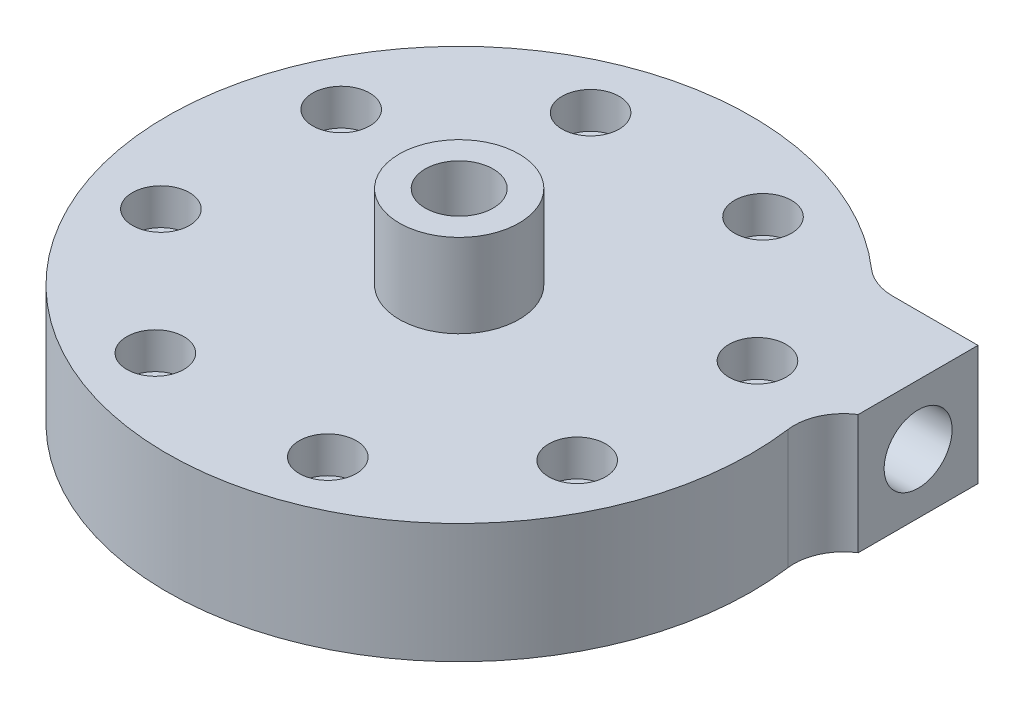
SolidWorks part; units mm, degrees
material "1060 Alloy"
ref_plane "Front" through (0, 0, 0) normal (0, 0, 1) x (1, 0, 0)
ref_plane "Top" through (0, 0, 0) normal (0, 1, 0) x (1, 0, 0)
ref_plane "Right" through (0, 0, 0) normal (1, 0, 0) x (0, 0, -1)
sketch "Sketch1" plane through (0, 0, 0) normal (0, 1, 0) x (1, 0, 0)
  line L0 (0, 0) -> (2.6731, 30.5538) construction
  line L1 (21.117, 30.6705) -> (50.1264, 33.2085) construction
  line L2 (11.6189, 28.3845) -> (50.1264, 28.3845) construction
  line L3 (21.117, 26.0945) -> (50.1264, 23.5565) construction
  line L4 (0, 0) -> (56.1418, -4.9118) construction
  line L5 (21.117, 30.6705) -> (21.117, 28.3845) construction
  line L6 (21.117, 28.3845) -> (21.117, 26.0945) construction
  line L7 (50.1264, 28.3845) -> (50.1264, 33.2085) construction
  line L8 (50.1264, 28.3845) -> (50.1264, 23.5565) construction
  line L9 (60.1264, 28.3845) -> (60.1264, 39.9329)
  line L10 (60.1264, 34.9329) -> (50.1264, 34.9329) construction
  line L11 (60.1264, 34.9329) -> (60.1264, 21.8361) construction
  line L12 (60.1264, 21.8361) -> (50.1264, 21.8361) construction
  line L13 (50.1264, 34.9329) -> (50.1264, 21.8361) construction
  line L14 (60.1264, 39.9329) -> (43.7019, 39.9329)
  line L15 (60.1264, 28.3845) -> (60.1264, 16.8361)
  line L17 (21.117, 30.6705) -> (0, 30.6705) construction
  line L18 (21.117, 26.0945) -> (16.117, 26.0945) construction
  arc A0 (37.1159, 42.408) -> (55.8478, 7.5534) centre (0, 0) ccw
  circle A1 centre (0, 0) radius 30.6705 construction
  arc A2 (55.8478, 7.5534) -> (60.1264, 16.8361) centre (65.2868, 8.8301) cw
  arc A3 (43.7019, 39.9329) -> (37.1159, 42.408) centre (43.7019, 49.9329) cw
  dimension "D1" = 112.7125
  dimension "D2" = 61.341
  dimension "D13" = 9.525
  dimension "D4" = 2.286
  dimension "D3" = 2.29
  dimension "D5" = 5
  dimension "D6" = 5
  dimension "D7" = 5
  dimension "D8" = 9.652
  dimension "D9" = 13.0969
  dimension "D10" = 10
  dimension "D11" = 5
  dimension "D14" = 5
  dimension "D12" = 5
extrude "main body" add sketch "Sketch1" along normal blind 23.0969
ref_plane "body midsection" through (0, 11.5484, 0) normal (0, 1, 0) x (1, 0, 0)
sketch "Sketch7" plane through (0, 23.0969, 0) normal (0, 1, 0) x (1, 0, 0)
  circle A0 centre (0, 0) radius 25.4
  dimension "D1" = 50.8
extrude "inlet boss" add sketch "Sketch7" along normal blind 50.8
sketch "Sketch3" plane through (0, 11.5484, 0) normal (0, 1, 0) x (1, 0, 0)
  line L0 (21.117, 30.6705) -> (0, 30.6705)
  line L1 (0, 30.6705) -> (0, 28.3845)
  line L2 (50.1264, 28.3845) -> (2.4833, 28.3845)
  line L3 (0, 0) -> (2.6731, 30.5538) construction
  line L4 (0, 28.3845) -> (2.4833, 28.3845)
  line L5 (50.1264, 33.2085) -> (50.1264, 34.9329)
  line L6 (50.1264, 34.9329) -> (60.1264, 34.9329)
  line L7 (60.1264, 34.9329) -> (60.1264, 28.3845)
  line L8 (60.1264, 28.3845) -> (50.1264, 28.3845)
  line L9 (21.117, 30.6705) -> (50.1264, 33.2085)
revolve "expansion cone and outlet" cut sketch "Sketch3" angle 360 about L2
sketch "Sketch2" plane through (0, 0, 0) normal (0, 0, 1) x (1, 0, 0)
  line L0 (-56.3562, 11.5484) -> (56.3562, 11.5484) construction
  line L1 (-56.3562, 23.0969) -> (-56.3562, 0) construction
  line L2 (56.3562, 0) -> (56.3562, 23.0969) construction
  line L3 (0, 0) -> (0, 23.0969) construction
  line L4 (25.4, 23.0969) -> (-25.4, 23.0969) construction
  line L5 (0, 18.6817) -> (0, 9.0936)
  line L6 (0, 9.0936) -> (26.67, 9.0936) construction
  line L7 (5.461, 18.6817) -> (5.565, 19.1708) construction
  line L8 (26.67, 14.1736) -> (5.461, 14.1736) construction
  line L9 (26.67, 9.0936) -> (26.67, 14.1736) construction
  line L10 (0, 19.1929) -> (0, 39.1929)
  line L11 (26.67, 14.1736) -> (5.461, 18.6817) construction
  line L12 (5.461, 18.6817) -> (0, 18.6817) construction
  line L13 (5.461, 18.6817) -> (5.461, 9.0936) construction
  line L14 (0, 9.0936) -> (0, 7.0936) construction
  line L15 (0, 7.0936) -> (26.67, 7.0936) construction
  line L16 (26.67, 7.0936) -> (26.67, 9.0936) construction
  line L17 (0, 9.0936) -> (0, 6.5936)
  line L18 (0, 7.0936) -> (0, 6.5936) construction
  line L19 (0, 6.5936) -> (26.67, 6.5936) construction
  line L20 (26.67, 6.5936) -> (26.67, 7.0936) construction
  line L21 (26.67, 6.5936) -> (30.6705, 6.5936) construction
  line L22 (30.6705, 6.5936) -> (30.6705, 13.3233)
  line L23 (26.67, 14.1736) -> (30.6705, 13.3233) construction
  line L24 (5.461, 18.6817) -> (5.461, 19.1929) construction
  line L25 (5.461, 19.1929) -> (0, 19.1929) construction
  line L26 (0, 19.1929) -> (0, 18.6817)
  line L27 (30.6705, 13.3233) -> (30.6705, 13.8344)
  line L28 (30.6705, 13.8344) -> (5.461, 19.1929)
  line L29 (0, 6.5936) -> (0, 0)
  line L30 (0, 0) -> (30.6705, 0)
  line L31 (-56.3562, 0) -> (56.3562, 0) construction
  line L32 (30.6705, 0) -> (30.6705, 6.5936)
  line L33 (30.6705, 13.8344) -> (0, 13.8344) construction
  line L34 (21.117, 13.8344) -> (0, 13.8344) construction
  line L35 (0, 39.1929) -> (6.5484, 39.1929) construction
  line L36 (6.5484, 39.1929) -> (6.5484, 29.1929)
  line L37 (6.5484, 29.1929) -> (5.461, 29.1929)
  line L38 (5.461, 29.1929) -> (5.461, 19.1929)
  line L39 (0, 39.1929) -> (0, 73.8969)
  line L40 (0, 73.8969) -> (25.4, 73.8969)
  line L41 (6.5484, 39.1929) -> (11.5484, 39.1929)
  line L42 (25.4, 73.8969) -> (-25.4, 73.8969) construction
  line L44 (11.5484, 39.1929) -> (11.5484, 23.0969)
  line L46 (25.4, 73.8969) -> (25.4, 23.0969)
  line L47 (25.4, 23.0969) -> (11.5484, 23.0969)
  dimension "D10" = 10
  dimension "D12" = 5
  dimension "D1" = 5.461
  dimension "D2" = 26.67
  dimension "D3" = 9.5881
  dimension "D4" = 5.08
  dimension "D5" = 2
  dimension "D6" = 4.0005
  dimension "D8" = 0.5
  dimension "D9" = 10
  dimension "D11" = 6.5484
revolve "main chamber" cut sketch "Sketch2" angle 360 about L5
sketch "Sketch5" plane through (0, 23.0969, 0) normal (0, 1, 0) x (1, 0, 0)
  line L1 (17.9206, 40.6775) -> (41.4351, 16.0915) construction
  line L3 (11.6189, 28.3845) -> (50.1264, 28.3845) construction
  circle A0 centre (0, 0) radius 44.45 construction
  circle A1 centre (41.4351, 16.0915) radius 2.9766
  circle A2 centre (0, 0) radius 44.45 construction
  circle A3 centre (40.6775, -17.9206) radius 2.9766
  circle A4 centre (0, 0) radius 44.45 construction
  circle A5 centre (16.0915, -41.4351) radius 2.9766
  circle A6 centre (0, 0) radius 44.45 construction
  circle A7 centre (-17.9206, -40.6775) radius 2.9766
  circle A8 centre (0, 0) radius 44.45 construction
  circle A9 centre (-41.4351, -16.0915) radius 2.9766
  circle A10 centre (0, 0) radius 44.45 construction
  circle A11 centre (-40.6775, 17.9206) radius 2.9766
  circle A12 centre (0, 0) radius 44.45 construction
  circle A13 centre (-16.0915, 41.4351) radius 2.9766
  circle A14 centre (0, 0) radius 44.45 construction
  circle A15 centre (17.9206, 40.6775) radius 2.9766
  point P5 (29.6778, 28.3845)
  point P30 (0, 0)
  dimension "D1" = 88.9
  dimension "D2" = 5.9531
  dimension "D4" = 8
sketch "Sketch6" plane through (0, 23.0969, 0) normal (0, 1, 0) x (1, 0, 0)
  circle A0 centre (41.4351, 16.0915) radius 5.5
  circle A1 centre (40.6775, -17.9206) radius 5.5
  circle A2 centre (16.0915, -41.4351) radius 5.5
  circle A3 centre (-17.9206, -40.6775) radius 5.5
  circle A4 centre (-41.4351, -16.0915) radius 5.5
  circle A5 centre (-40.6775, 17.9206) radius 5.5
  circle A6 centre (-16.0915, 41.4351) radius 5.5
  circle A7 centre (17.9206, 40.6775) radius 5.5
  point P19 (0, 0)
  dimension "D1" = 11
  dimension "D2" = 8
ref_plane "exit axial plane" through (0, 0, -28.3845) normal (0, 0, -1) x (-1, 0, 0)
extrude "bolt clearances" cut sketch "Sketch5" against normal through all
extrude "bolt head clearance" cut sketch "Sketch6" against normal blind 7
equation "\"bearing OD\" = 30mm"
equation "\"bearing ID\"= 10mm"
equation "\"bearing depth\"= 9mm"
equation "\"bearing outer race thickness\"= 1mm"
equation "\"bearing inner race thickness\"= 1mm"
equation "\"bearing bore\" = \"bearing depth\" + 1mm"
equation "\"z\" = 8\t\t\t\t'number of blades"
equation "\"de\" = 0.43in\t\t\t'entrance eye diameter"
equation "\"d2\" = 2.1in \t\t\t'outer diameter of the impeller"
equation "\"d_exit\" = 0.18in \t\t'throat aka d1"
equation "\"theta\" = 12\t\t\t'angle of blades from inner to outer "
equation "\"b2\" = .2in\t\t\t'tip height from disc surface at d2; slightly higher than d_exit"
equation "\"b1\" = \"b2\" + (\"d2\"/2 - \"de\"/2)*tan(\"theta\") \t\t\t'tip height from disc surface at inlet eye"
equation "\"s\"=\"ce\" - \"z\"*\"s_open\""
equation "\"impeller upper clearance\"= .5mm"
equation "\"impeller horizontal clearance\"= (\"d2\"*1.15 - \"d2\")/2 \t\t'clearance based on D2-D3 ratio for circular volute, ranges 1.15 to 1.2"
equation "\"impeller bottom clearance\"= .5mm"
equation "\"impeller base thickness\"= 2mm"
equation "\"impeller dowel diameter\" = 2mm"
equation "\"impeller bolt head diameter\" = \"m4 head bore diameter\""
equation "\"impeller bolt head depth\" = 4mm"
equation "\"impeller bolt stop depth\" = 3mm"
equation "\"impeller bolt bore\" = \"m4 clearance\""
equation "\"impeller shaft bore depth\" = 12mm"
equation "\"impeller shaft bore\" = 8mm"
equation "\"impeller boss depth\" = \"impeller shaft bore depth\"+\"impeller bolt stop depth\"+\"impeller bolt head depth\"-\"impeller base thickness\""
equation "\"impeller boss diameter\" = \"upper seal ID\""
equation "\"impeller dowel length\" = 2mm*2 + \"impeller shaft bore\""
equation "\"coupler motor shaft hole ID\"= 8mm"
equation "\"coupler OD\"= 17mm"
equation "\"coupler length\"= 25mm"
equation "\"motor OD\" = 64mm"
equation "\"motor shaft diameter\"= 8mm"
equation "\"motor shaft pride\"= 32mm"
equation "\"motor to bearing plate distance\" = \"motor shaft pride\" + 2mm +\"coupler length\"/2"
equation "\"square plate bolt bore\" = \"m8 clearance\""
equation "\"square plate bolt head diameter\" = 13.5mm"
equation "\"square plate bolt head depth\" = 8mm"
equation "\"square plate bolt pattern diameter\"= 3.5in"
equation "\"motor mount center bore\"= \"coupler OD\"+ 4mm"
equation "\"motor mount post radius\"= ( 3 * \"square plate bolt bore\" ) / 2"
equation "\"motor mount m4 screw hole diameter\"= 4mm"
equation "\"motor mount m4 head diameter\"= 7.25mm"
equation "\"motor mount m4 head depth\"= 4mm"
equation "\"motor mount m4 pattern diamater\" = 30mm"
equation "\"motor mount plate thickness\"= 8mm + \"motor mount m4 head depth\""
equation "\"bearing plate stop ID\" = \"bearing OD\" - 4mm"
equation "\"bearing plate stop depth\" = 3mm"
equation "\"bearing plate thickness\" = \"bearing bore\" + \"bearing plate stop depth\" + \"shaft bearing stop length\""
equation "\"shaft coupler section diameter\" = 8mm"
equation "\"shaft coupler section length\" = \"motor to bearing plate distance\" - \"motor shaft pride\" - 2mm"
equation "\"shaft bearing section diameter\" = \"bearing ID\""
equation "\"shaft bearing section length\" = \"bearing plate stop depth\" + \"bearing depth\""
equation "\"shaft bearing stop diameter\" = \"bearing ID\" + 4mm"
equation "\"shaft bearing stop length\" = 3mm"
equation "\"impeller cavity center height\"= \"impeller bottom clearance\" + \"impeller upper clearance\" + \"impeller center height\""
equation "\"impeller cavity diameter\"= 2 * \"impeller horizontal clearance\" + \"d2\" \t\t\t\t\t\t\t\t\t'called D3 analytically"
equation "\"impeller cavity outer height\"= \"impeller bottom clearance\" + \"impeller upper clearance\" + \"impeller base thickness\" + \"b2\" \t\t'this is height at impeller diameter d2, not at d3"
equation "\"impeller housing thickness\"= \"impeller housing exit threaded diameter\" + 2*\"impeller housing outlet grip\""
equation "\"impeller housing diameter\" = \"square plate bolt pattern diameter\" + 2*\"motor mount post radius\""
equation "\"impeller housing bolt count\" = 8"
equation "\"impeller housing bolt diameter\" = \"m6 clearance\""
equation "\"impeller housing bolt pattern diameter\" = 3.5in"
equation "\"impeller housing threaded inlet diameter\" = 0.515625in \t'this is the 33/64 drill size for 9/16-18 fitting, expecting swagelok SS-8FK0-1-6STH fitting"
equation "\"impeller housing threaded inlet depth\"= 10mm"
equation "\"impeller housing exit threaded diameter\"= 0.515625in \t\t'this is the 33/64 drill size for 9/16-18 fitting, expecting swagelok SS-8FK0-1-6STH fitting"
equation "\"impeller housing exit threaded depth\"= 10mm"
equation "\"impeller housing diffuser conical angle\"=10"
equation "\"impeller housing diffuser tangent angle\"=5"
equation "\"impeller housing diffuser final diameter\" = .38in"
equation "\"impeller housing outlet grip\" = 5mm"
equation "\"D1@Sketch1\"=\"impeller housing diameter\""
equation "\"D2@Sketch1\"=\"impeller cavity diameter\""
equation "\"D4@Sketch1\"=\"d_exit\"/2"
equation "\"D5@Sketch1\"=\"impeller housing diffuser tangent angle\""
equation "\"D6@Sketch1\"=\"impeller housing diffuser conical angle\"/2"
equation "\"D7@Sketch1\"=\"impeller housing diffuser conical angle\"/2"
equation "\"D8@Sketch1\"=\"impeller housing diffuser final diameter\""
equation "\"D9@Sketch1\"=\"impeller housing exit threaded diameter\""
equation "\"D10@Sketch1\"=\"impeller housing exit threaded depth\""
equation "\"D11@Sketch1\"=\"impeller housing outlet grip\""
equation "\"D1@main body\" = \"impeller housing thickness\""
equation "\"de_length\" = 10mm\t\t'entrance eye consistent length"
equation "\"D1@Sketch5\"=\"impeller housing bolt pattern diameter\""
equation "\"D2@Sketch5\"=\"m6 clearance\""
equation "\"end mill size\" = 0.375in\t'for 3/8 endmill"
equation "\"ae\" = 3.14*(\"de\"^2)/4\t\t'entrance eye area'"
equation "\"ce\" = 3.14*\"de\"\t\t'entrance eye circumference"
equation "\"av_ratio\" = .325\t\t'ratio of av/ae at N_s of 470, range is .275 to .375, .325 ideal. High ratio means bigger area means smaller blades"
equation "\"av\" = \"ae\"*\"av_ratio\"\t\t'area between just two blades"
equation "\"s_open\" = \"av\"/\"b1\"\t\t'width of open area"
equation "\"impeller center height\" = \"impeller base thickness\" + \"b1\"\t'impeller height at de"
equation "\"impeller outer height\" = \"impeller base thickness\" + \"b2\"\t'impeller height at de"
equation "\"shaft impeller section diameter\" = \"impeller shaft bore\""
equation "\"shaft impeller section length\" = \"upper seal plate thickness\" + \"upper seal plate riser\" + \"impeller bottom clearance\" + \"impeller base thickness\" - \"impeller bolt head depth\" - \"impeller bolt stop depth\""
equation "\"m6 clearance\" = 0.234375in\t'this is 15/64 bit = 5.95mm, could use 6mm bit, B bit for 6.04mm or 1/4 bit for 6.35mm"
equation "\"m6 tap\" = 5mm\t\t\t'5mm is appropriate, could use 13/64 or #5,6,7"
equation "\"m6 head bore diameter\" = 11mm\t\t"
equation "\"m6 head bore depth\" = 7mm\t'actual is 6mm"
equation "\"m8 clearance\" = 0.3125in\t'this is 5/16in for 7.93mm, could use 8mm, O,P, or 21/64"
equation "\"m8 tap\" = 0.265625in\t\t'this is 17/64 for 6.746875mm"
equation "\"m8 head bore diameter\" = 14mm"
equation "\"m8 head bore depth\" = 9mm\t'actual is 8mm"
equation "\"D1@Sketch6\"=\"m6 head bore diameter\""
equation "\"D1@bolt head clearance\" = \"m6 head bore depth\""
equation "\"lower seal OD\" = .917in\t\t'this is https://www.mcmaster.com/#9281k121/=174001b"
equation "\"lower seal ID\"= .375in"
equation "\"lower seal depth\" = .625in + .218in"
equation "\"lower seal bore\" = \"lower seal depth\" + 1mm"
equation "\"upper seal OD\" = 1.125in\t'this is https://www.mcmaster.com/#5154t33/=173zuau, needs to be visually inspected before machining!"
equation "\"upper seal ID\"= 0.625in"
equation "\"upper seal depth\"= .25in\t'aka height; these values need to be confirmed by inspection!! We may want to compress the height."
equation "\"upper seal bore\" = \"upper seal depth\" + 1mm"
equation "\"big o-ring thickness\" = .139in"
equation "\"big o-ring OD\" = 2.734in"
equation "\"big o-ring ID\" = 3.012in"
equation "\"big o-ring groove depth\" = \"big o-ring thickness\"*4/5"
equation "\"lower seal plate lip depth\" = 2mm"
equation "\"lower seal plate lip ID\" = \"lower seal OD\" - 3mm"
equation "\"lower seal plate thickness\" = \"lower seal plate lip depth\" + \"lower seal bore\""
equation "\"shaft lower seal section diameter\" = \"lower seal ID\""
equation "\"shaft lower seal section length\" = \"lower seal plate thickness\" + 1mm"
equation "\"upper seal plate thickness\" = \"upper seal plate pressure hole diameter\"+10mm"
equation "\"upper seal plate lip ID\" = \"upper seal OD\" - 3mm"
equation "\"upper seal plate riser\" = 6.59mm \t\t'this number needs to be read from the housing file"
equation "\"upper seal plate pressure hole diameter\" = .125in\t'this is 1/8 drill "
equation "\"upper seal plate pressure tap diameter\" = .328125in \t'this is 21/64 drill for a 1/8 ANPT tap"
equation "\"upper seal plate pressure tap grip\" = 5mm\t\t'this is the area around the tap so it doesn't crack"
equation "\"upper seal plate pressure tap depth\" = 12"
equation "\"m4 clearance\" = 0.171875in \t'this is 11/64 bit for 4.36mm"
equation "\"m4 tap\" = 0.125in\t\t'this is 1/8 bit for 3.17mm"
equation "\"m4 head bore diameter\" = 7.5mm"
equation "\"m4 head bore depth\" = 5mm\t'actual is ~4mm"
equation "\"D1@Sketch2\"=\"de\"/2"
equation "\"D3@Sketch2\"=\"b1\""
equation "\"D4@Sketch2\"=\"b2\""
equation "\"D2@Sketch2\"=\"d2\"/2"
equation "\"D5@Sketch2\"=\"impeller base thickness\""
equation "\"D6@Sketch2\"=\"impeller horizontal clearance\""
equation "\"D7@Sketch2\"=\"impeller bottom clearance\""
equation "\"D8@Sketch2\"=\"impeller upper clearance\""
equation "\"D9@Sketch2\"=\"de_length\""
equation "\"D10@Sketch2\"=\"impeller housing threaded inlet depth\""
equation "\"D11@Sketch2\"=\"impeller housing threaded inlet diameter\"/2"
equation "\"D12@Sketch2\"=\"impeller housing outlet grip\""
equation "\"min blade thickness\" = .15in"
equation "\"l_exit\"= 5mm\t\t\t'length of eye entrance"
equation "\"D12@Sketch1\"=\"impeller housing outlet grip\""
equation "\"D13@Sketch1\"=\"end mill size\""
